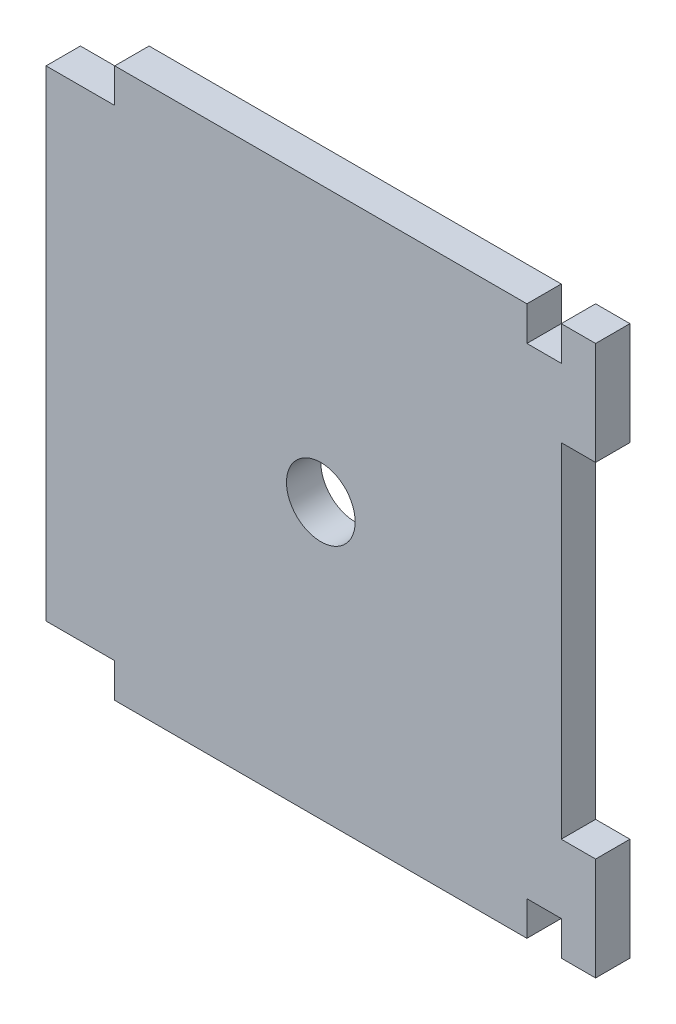
SolidWorks part; units mm, degrees
material "Balsa"
ref_plane "Plan de face" through (0, 0, 0) normal (0, 0, 1) x (1, 0, 0)
ref_plane "Plan de dessus" through (0, 0, 0) normal (0, 1, 0) x (1, 0, 0)
ref_plane "Plan de droite" through (0, 0, 0) normal (1, 0, 0) x (0, 0, -1)
sketch "Esquisse1" plane through (0, 0, 0) normal (0, 0, 1) x (1, 0, 0)
  line L0 (40, 40) -> (80, 40) construction
  line L1 (80, 80) -> (0, 80)
  line L2 (80, 80) -> (80, 0)
  line L3 (80, 0) -> (0, 0)
  line L4 (0, 80) -> (0, 0)
  line L5 (40, 80) -> (40, 40) construction
  circle A0 centre (40, 40) radius 5
  dimension "D3" = 10
  dimension "D1" = 80
  dimension "D2" = 80
extrude "Boss.-Extru.1" add sketch "Esquisse1" along normal blind 5
sketch "Esquisse2" plane through (0, 0, 5) normal (0, 0, 1) x (1, 0, 0)
  line L0 (0, 0) -> (80, 0) construction
  line L1 (0, 0) -> (10, 0)
  line L2 (0, 0) -> (0, 5)
  line L3 (0, 5) -> (10, 5)
  line L4 (10, 0) -> (10, 5)
  line L5 (0, 80) -> (0, 0) construction
  line L6 (0, 40) -> (80, 40) construction
  line L7 (80, 0) -> (80, 80) construction
  line L8 (40, 80) -> (40, 0.9116) construction
  line L9 (80, 80) -> (0, 80) construction
  line L10 (10, 80) -> (10, 75)
  line L11 (0, 75) -> (10, 75)
  line L12 (0, 80) -> (0, 75)
  line L13 (0, 80) -> (10, 80)
  line L14 (80, 15) -> (75, 15)
  line L15 (80, 65) -> (75, 65)
  line L16 (75, 15) -> (75, 65)
  line L17 (80, 65) -> (80, 15)
  line L18 (70, 80) -> (70, 75)
  line L19 (75, 0) -> (70, 0)
  line L20 (75, 0) -> (75, 5)
  line L21 (75, 5) -> (70, 5)
  line L22 (70, 0) -> (70, 5)
  line L23 (75, 75) -> (70, 75)
  line L24 (75, 80) -> (75, 75)
  line L25 (75, 80) -> (70, 80)
  dimension "D1" = 5
  dimension "D2" = 10
  dimension "D3" = 5
  dimension "D4" = 50
  dimension "D5" = 5
  dimension "D6" = 5
  dimension "D7" = 5
extrude "Créneaux -" cut sketch "Esquisse2" against normal blind 5
